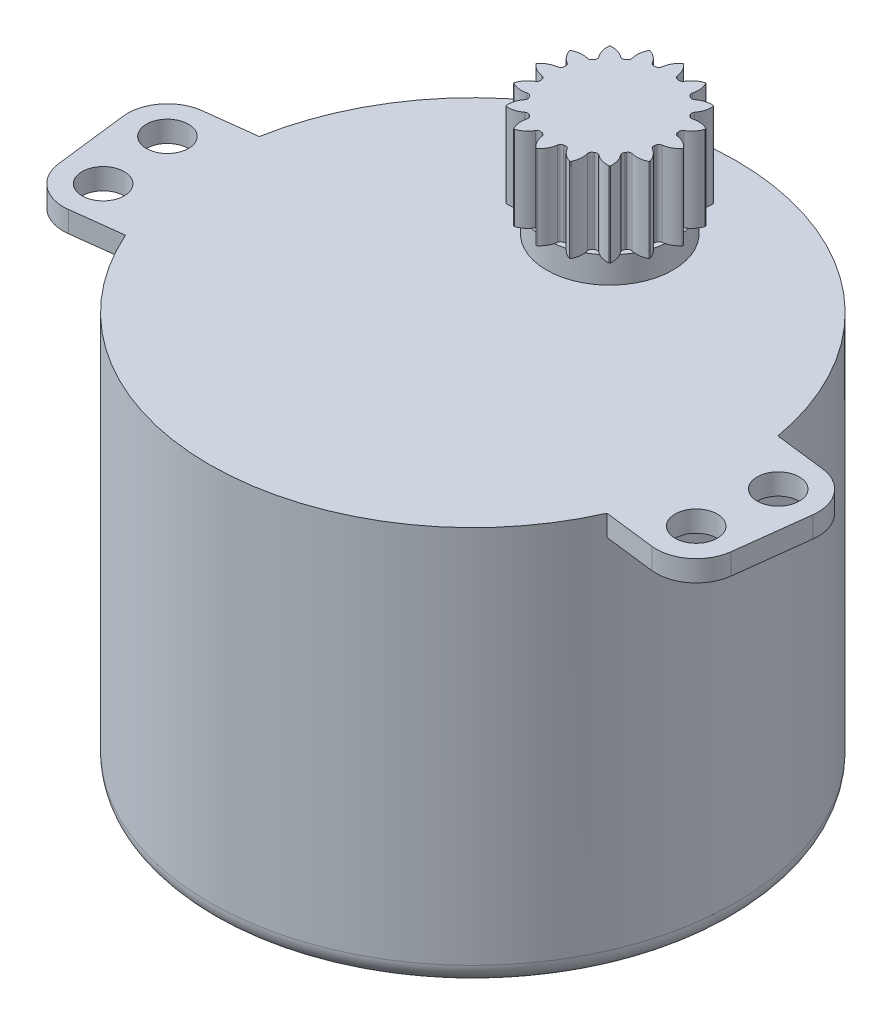
SolidWorks part; units mm, degrees
ref_plane "Ön Düzlem" through (0, 0, 0) normal (0, 0, 1) x (1, 0, 0)
ref_plane "Üst Düzlem" through (0, 0, 0) normal (0, 1, 0) x (1, 0, 0)
ref_plane "Sağ Düzlem" through (0, 0, 0) normal (1, 0, 0) x (0, 0, -1)
sketch "Sketch1" plane through (0, 0, 0) normal (0, 1, 0) x (1, 0, 0)
  circle A0 centre (0, 0) radius 25
  dimension "D1" = 50
extrude "Boss-Extrude1" add sketch "Sketch1" along normal blind 38
fillet "Fillet1" radius 2 1 edges at (0, 0, 25)
sketch "Sketch2" plane through (0, 38, 0) normal (0, 1, 0) x (1, 0, 0)
  line L0 (0, 25) -> (0, 0) construction
  circle A0 centre (0, 0) radius 25 construction
  circle A1 centre (0, 13) radius 6
  dimension "D1" = 12
  dimension "D2" = 12
extrude "Boss-Extrude2" add sketch "Sketch2" along normal blind 2.5
sketch "Sketch3" plane through (0, 40.5, 0) normal (0, 1, 0) x (1, 0, 0)
  circle A0 centre (0, 13) radius 7
  dimension "D1" = 14
extrude "Boss-Extrude3" add sketch "Sketch3" along normal blind 8
sketch "Sketch4" plane through (0, 48.5, 0) normal (0, 1, 0) x (1, 0, 0)
  line L0 (0, 20) -> (0, 13) construction
  arc A0 (-3.0047, 17.6067) -> (-3.1062, 17.5389) centre (0, 13) ccw
  circle A1 centre (0, 13) radius 7 construction
  arc A2 (-0.0658, 19.945) -> (-0.7327, 18.7017) centre (1.25, 18.4387) ccw
  arc A3 (0.0658, 19.945) -> (0.7327, 18.7017) centre (-1.25, 18.4387) cw
  arc A4 (-0.0658, 19.945) -> (0.0658, 19.945) centre (0, 19.8697) cw
  arc A5 (2.5969, 19.4415) -> (1.505, 18.548) centre (3.2361, 17.5464) ccw
  arc A6 (2.7185, 19.3911) -> (2.8588, 17.9873) centre (0.9265, 18.5031) cw
  arc A7 (2.5969, 19.4415) -> (2.7185, 19.3911) centre (2.6289, 19.3467) cw
  arc A8 (4.8643, 17.9574) -> (3.5136, 17.5498) centre (4.7296, 15.9619) ccw
  arc A9 (4.9574, 17.8643) -> (4.5498, 16.5136) centre (2.9619, 17.7296) cw
  arc A10 (4.8643, 17.9574) -> (4.9574, 17.8643) centre (4.8576, 17.8576) cw
  arc A11 (6.3911, 15.7185) -> (4.9873, 15.8588) centre (5.5031, 13.9265) ccw
  arc A12 (6.4415, 15.5969) -> (5.548, 14.505) centre (4.5464, 16.2361) cw
  arc A13 (6.3911, 15.7185) -> (6.4415, 15.5969) centre (6.3467, 15.6289) cw
  arc A14 (6.945, 13.0658) -> (5.7017, 13.7327) centre (5.4387, 11.75) ccw
  arc A15 (6.945, 12.9342) -> (5.7017, 12.2673) centre (5.4387, 14.25) cw
  arc A16 (6.945, 13.0658) -> (6.945, 12.9342) centre (6.8697, 13) cw
  arc A17 (6.4415, 10.4031) -> (5.548, 11.495) centre (4.5464, 9.7639) ccw
  arc A18 (6.3911, 10.2815) -> (4.9873, 10.1412) centre (5.5031, 12.0735) cw
  arc A19 (6.4415, 10.4031) -> (6.3911, 10.2815) centre (6.3467, 10.3711) cw
  arc A20 (4.9574, 8.1357) -> (4.5498, 9.4864) centre (2.9619, 8.2704) ccw
  arc A21 (4.8643, 8.0426) -> (3.5136, 8.4502) centre (4.7296, 10.0381) cw
  arc A22 (4.9574, 8.1357) -> (4.8643, 8.0426) centre (4.8576, 8.1424) cw
  arc A23 (2.7185, 6.6089) -> (2.8588, 8.0127) centre (0.9265, 7.4969) ccw
  arc A24 (2.5969, 6.5585) -> (1.505, 7.452) centre (3.2361, 8.4536) cw
  arc A25 (2.7185, 6.6089) -> (2.5969, 6.5585) centre (2.6289, 6.6533) cw
  arc A26 (0.0658, 6.055) -> (0.7327, 7.2983) centre (-1.25, 7.5613) ccw
  arc A27 (-0.0658, 6.055) -> (-0.7327, 7.2983) centre (1.25, 7.5613) cw
  arc A28 (0.0658, 6.055) -> (-0.0658, 6.055) centre (0, 6.1303) cw
  arc A29 (-2.5969, 6.5585) -> (-1.505, 7.452) centre (-3.2361, 8.4536) ccw
  arc A30 (-2.7185, 6.6089) -> (-2.8588, 8.0127) centre (-0.9265, 7.4969) cw
  arc A31 (-2.5969, 6.5585) -> (-2.7185, 6.6089) centre (-2.6289, 6.6533) cw
  arc A32 (-4.8643, 8.0426) -> (-3.5136, 8.4502) centre (-4.7296, 10.0381) ccw
  arc A33 (-4.9574, 8.1357) -> (-4.5498, 9.4864) centre (-2.9619, 8.2704) cw
  arc A34 (-4.8643, 8.0426) -> (-4.9574, 8.1357) centre (-4.8576, 8.1424) cw
  arc A35 (-6.3911, 10.2815) -> (-4.9873, 10.1412) centre (-5.5031, 12.0735) ccw
  arc A36 (-6.4415, 10.4031) -> (-5.548, 11.495) centre (-4.5464, 9.7639) cw
  arc A37 (-6.3911, 10.2815) -> (-6.4415, 10.4031) centre (-6.3467, 10.3711) cw
  arc A38 (-6.945, 12.9342) -> (-5.7017, 12.2673) centre (-5.4387, 14.25) ccw
  arc A39 (-6.945, 13.0658) -> (-5.7017, 13.7327) centre (-5.4387, 11.75) cw
  arc A40 (-6.945, 12.9342) -> (-6.945, 13.0658) centre (-6.8697, 13) cw
  arc A41 (-6.4415, 15.5969) -> (-5.548, 14.505) centre (-4.5464, 16.2361) ccw
  arc A42 (-6.3911, 15.7185) -> (-4.9873, 15.8588) centre (-5.5031, 13.9265) cw
  arc A43 (-6.4415, 15.5969) -> (-6.3911, 15.7185) centre (-6.3467, 15.6289) cw
  arc A44 (-4.9574, 17.8643) -> (-4.5498, 16.5136) centre (-2.9619, 17.7296) ccw
  arc A45 (-4.8643, 17.9574) -> (-3.5136, 17.5498) centre (-4.7296, 15.9619) cw
  arc A46 (-4.9574, 17.8643) -> (-4.8643, 17.9574) centre (-4.8576, 17.8576) cw
  arc A47 (-2.7185, 19.3911) -> (-2.8588, 17.9873) centre (-0.9265, 18.5031) ccw
  arc A48 (-2.5969, 19.4415) -> (-1.505, 18.548) centre (-3.2361, 17.5464) cw
  arc A49 (-2.7185, 19.3911) -> (-2.5969, 19.4415) centre (-2.6289, 19.3467) cw
  arc A50 (-1.013, 18.4059) -> (-1.1328, 18.3821) centre (0, 13) ccw
  arc A51 (1.1328, 18.3821) -> (1.013, 18.4059) centre (0, 13) ccw
  arc A52 (3.1062, 17.5389) -> (3.0047, 17.6067) centre (0, 13) ccw
  arc A53 (4.6067, 16.0047) -> (4.5389, 16.1062) centre (0, 13) ccw
  arc A54 (5.4059, 14.013) -> (5.3821, 14.1328) centre (0, 13) ccw
  arc A55 (5.3821, 11.8672) -> (5.4059, 11.987) centre (0, 13) ccw
  arc A56 (4.5389, 9.8938) -> (4.6067, 9.9953) centre (0, 13) ccw
  arc A57 (3.0047, 8.3933) -> (3.1062, 8.4611) centre (0, 13) ccw
  arc A58 (1.013, 7.5941) -> (1.1328, 7.6179) centre (0, 13) ccw
  arc A59 (-1.1328, 7.6179) -> (-1.013, 7.5941) centre (0, 13) ccw
  arc A60 (-3.1062, 8.4611) -> (-3.0047, 8.3933) centre (0, 13) ccw
  arc A61 (-4.6067, 9.9953) -> (-4.5389, 9.8938) centre (0, 13) ccw
  arc A62 (-5.4059, 11.987) -> (-5.3821, 11.8672) centre (0, 13) ccw
  arc A63 (-5.3821, 14.1328) -> (-5.4059, 14.013) centre (0, 13) ccw
  arc A64 (-4.5389, 16.1062) -> (-4.6067, 16.0047) centre (0, 13) ccw
  arc A65 (-3.0047, 17.6067) -> (-2.8588, 17.9873) centre (-3.1944, 17.8977) ccw
  arc A66 (-3.1062, 17.5389) -> (-3.5136, 17.5498) centre (-3.3024, 17.8255) cw
  arc A67 (-4.5389, 16.1062) -> (-4.5498, 16.5136) centre (-4.8255, 16.3024) ccw
  arc A68 (-4.6067, 16.0047) -> (-4.9873, 15.8588) centre (-4.8977, 16.1944) cw
  arc A69 (-5.3821, 14.1328) -> (-5.548, 14.505) centre (-5.722, 14.2044) ccw
  arc A70 (-5.4059, 14.013) -> (-5.7017, 13.7327) centre (-5.7473, 14.077) cw
  arc A71 (-5.3821, 11.8672) -> (-5.548, 11.495) centre (-5.722, 11.7956) cw
  arc A72 (-5.4059, 11.987) -> (-5.7017, 12.2673) centre (-5.7473, 11.923) ccw
  arc A73 (-4.5389, 9.8938) -> (-4.5498, 9.4864) centre (-4.8255, 9.6976) cw
  arc A74 (-4.6067, 9.9953) -> (-4.9873, 10.1412) centre (-4.8977, 9.8056) ccw
  arc A75 (-3.0047, 8.3933) -> (-2.8588, 8.0127) centre (-3.1944, 8.1023) cw
  arc A76 (-3.1062, 8.4611) -> (-3.5136, 8.4502) centre (-3.3024, 8.1745) ccw
  arc A77 (-1.1328, 7.6179) -> (-1.505, 7.452) centre (-1.2044, 7.278) ccw
  arc A78 (-0.7327, 7.2983) -> (-1.013, 7.5941) centre (-1.077, 7.2527) ccw
  arc A79 (0.7327, 7.2983) -> (1.013, 7.5941) centre (1.077, 7.2527) cw
  arc A80 (1.505, 7.452) -> (1.1328, 7.6179) centre (1.2044, 7.278) ccw
  arc A81 (2.8588, 8.0127) -> (3.0047, 8.3933) centre (3.1944, 8.1023) cw
  arc A82 (3.1062, 8.4611) -> (3.5136, 8.4502) centre (3.3024, 8.1745) cw
  arc A83 (4.5498, 9.4864) -> (4.5389, 9.8938) centre (4.8255, 9.6976) cw
  arc A84 (4.6067, 9.9953) -> (4.9873, 10.1412) centre (4.8977, 9.8056) cw
  arc A85 (5.3821, 11.8672) -> (5.548, 11.495) centre (5.722, 11.7956) ccw
  arc A86 (5.4059, 11.987) -> (5.7017, 12.2673) centre (5.7473, 11.923) cw
  arc A87 (5.4059, 14.013) -> (5.7017, 13.7327) centre (5.7473, 14.077) ccw
  arc A88 (5.3821, 14.1328) -> (5.548, 14.505) centre (5.722, 14.2044) cw
  arc A89 (4.9873, 15.8588) -> (4.6067, 16.0047) centre (4.8977, 16.1944) cw
  arc A90 (4.5389, 16.1062) -> (4.5498, 16.5136) centre (4.8255, 16.3024) cw
  arc A91 (3.5136, 17.5498) -> (3.1062, 17.5389) centre (3.3024, 17.8255) cw
  arc A92 (3.0047, 17.6067) -> (2.8588, 17.9873) centre (3.1944, 17.8977) cw
  arc A93 (1.1328, 18.3821) -> (1.505, 18.548) centre (1.2044, 18.722) ccw
  arc A94 (1.013, 18.4059) -> (0.7327, 18.7017) centre (1.077, 18.7473) cw
  arc A95 (-1.1328, 18.3821) -> (-1.505, 18.548) centre (-1.2044, 18.722) cw
  arc A96 (-1.013, 18.4059) -> (-0.7327, 18.7017) centre (-1.077, 18.7473) ccw
  circle A97 centre (0, 13) radius 7
  circle A98 centre (0, 13) radius 5.5 construction
  point P121 (0, 13)
  point P178 (0.75, 18.4486)
  point P183 (-0.75, 18.4486)
  dimension "D1" = 1.5
  dimension "D3" = 2
  dimension "D4" = 0.1
  dimension "D6" = 0.3474
  dimension "D2" = 1.5
  dimension "D5" = 16
extrude "Cut-Extrude1" cut sketch "Sketch4" against normal blind 8
sketch "Sketch5" plane through (0, 38, 0) normal (0, 1, 0) x (1, 0, 0)
  line L0 (-28.1552, -6.9488) -> (0, 0) construction
  line L1 (0, 0) -> (-29, 0) construction
  line L2 (-29, 0) -> (-28.1552, -6.9488) construction
  line L3 (-29, 0) -> (-28.1552, -6.9488) construction
  line L4 (0, 0) -> (0, -25) construction
  line L5 (-32.7603, -0.4572) -> (-31.9155, -7.406)
  line L6 (-29.4572, 3.7603) -> (-24.6189, 4.3486)
  line L7 (-27.698, -10.7092) -> (-22.8597, -10.1209)
  line L8 (-29.4572, 3.7603) -> (-27.698, -10.7092) construction
  line L9 (29.4572, 3.7603) -> (24.6189, 4.3486)
  line L10 (32.7603, -0.4572) -> (31.9155, -7.406)
  line L11 (27.698, -10.7092) -> (22.8597, -10.1209)
  circle A0 centre (-29, 0) radius 2
  circle A1 centre (-28.1552, -6.9488) radius 2
  arc A2 (-29.4572, 3.7603) -> (-32.7603, -0.4572) centre (-29, 0) ccw
  arc A3 (-31.9155, -7.406) -> (-27.698, -10.7092) centre (-28.1552, -6.9488) ccw
  circle A4 centre (0, 0) radius 25 construction
  arc A5 (-24.6189, 4.3486) -> (-22.8597, -10.1209) centre (0, 0) ccw
  arc A6 (29.4572, 3.7603) -> (32.7603, -0.4572) centre (29, 0) cw
  arc A7 (31.9155, -7.406) -> (27.698, -10.7092) centre (28.1552, -6.9488) cw
  circle A8 centre (29, 0) radius 2
  circle A9 centre (28.1552, -6.9488) radius 2
  arc A10 (24.6189, 4.3486) -> (22.8597, -10.1209) centre (0, 0) cw
  point P6 (-28.5776, -3.4744)
  dimension "D3" = 4
  dimension "D4" = 3.788
  dimension "D5" = 3.788
  dimension "D1" = 29
  dimension "D2" = 7
  dimension "D6" = 3.788
  dimension "D7" = 14.576
  dimension "D8" = 14.4695
extrude "Boss-Extrude4" add sketch "Sketch5" against normal blind 2
sketch "Sketch6" plane through (0, 0, 0) normal (0, -1, 0) x (1, 0, 0)
  line L0 (-23, 0) -> (23, 0) construction
  line L1 (-5, 2) -> (5, 2)
  line L2 (-5, 2) -> (-5, -2)
  line L3 (-5, -2) -> (5, -2)
  line L4 (5, 2) -> (5, -2)
  line L5 (0, 0) -> (0, -23) construction
  circle A0 centre (0, 0) radius 23 construction
  dimension "D1" = 10
  dimension "D2" = 4
extrude "Cut-Extrude2" cut sketch "Sketch6" against normal blind 4
